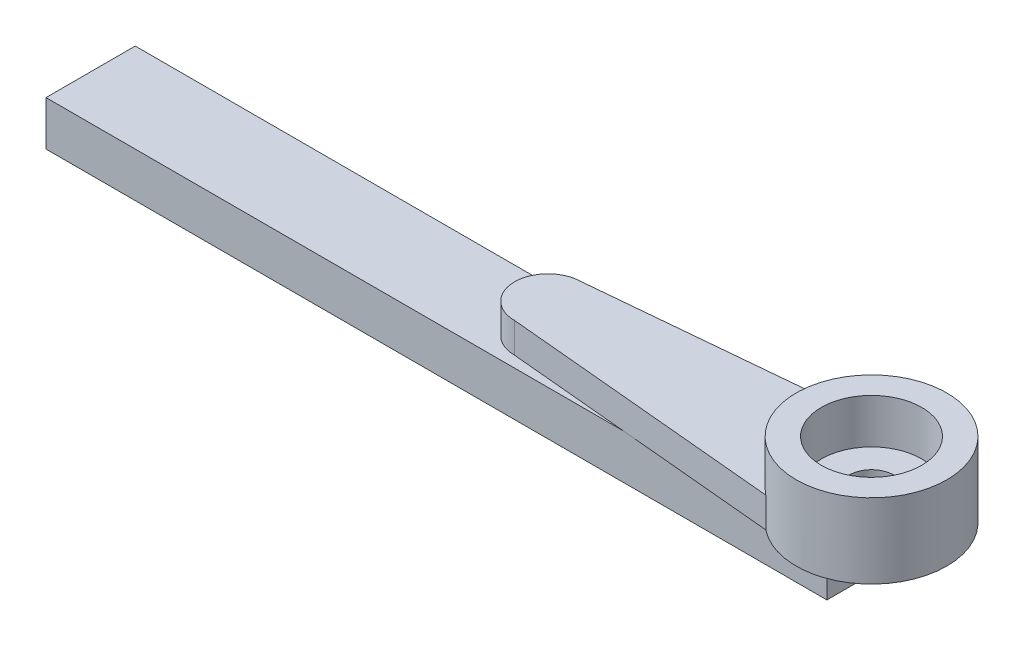
SolidWorks part; units mm, degrees
ref_plane "Piano frontale" through (0, 0, 0) normal (0, 0, 1) x (1, 0, 0)
ref_plane "Piano superiore" through (0, 0, 0) normal (0, 1, 0) x (1, 0, 0)
ref_plane "Piano destro" through (0, 0, 0) normal (1, 0, 0) x (0, 0, -1)
sketch "Schizzo1" plane through (0, 0, 0) normal (0, 1, 0) x (1, 0, 0)
  line L0 (-2.09, 2.65) -> (-14.5, 1.5)
  line L1 (-2.09, -2.65) -> (-14.5, -1.5)
  line L2 (-2.09, 2.65) -> (-2.09, -2.65)
  circle A0 centre (0, 0) radius 3.375
  arc A1 (-14.5, 1.5) -> (-14.5, -1.5) centre (-14.5, 0) ccw
  point P8 (-2.09, 0)
  point P13 (-16, 0)
  dimension "D1" = 6.75
  dimension "D3" = 1.5
  dimension "D2" = 5.3
  dimension "D4" = 3
  dimension "D5" = 16
extrude "Estrusione-Estrusione1" add sketch "Schizzo1" along normal blind 1.35 contours L0 A1 L1 A0 | L2 A0 | L2 A0
sketch "Schizzo2" plane through (0, 1.35, 0) normal (0, 1, 0) x (1, 0, 0)
  circle A0 centre (0, 0) radius 3.375
extrude "Estrusione-Estrusione2" add sketch "Schizzo2" along normal blind 2
sketch "Schizzo3" plane through (0, 3.35, 0) normal (0, 1, 0) x (1, 0, 0)
  circle A0 centre (0, 0) radius 2.25
  dimension "D1" = 4.5
extrude "Taglio-Estrusione1" cut sketch "Schizzo3" against normal blind 2
sketch "Schizzo4" plane through (0, 1.35, 0) normal (0, 1, 0) x (1, 0, 0)
  circle A0 centre (0, 0) radius 1
  dimension "D1" = 2
extrude "Taglio-Estrusione2" cut sketch "Schizzo4" against normal through all
sketch "Schizzo6" plane through (0, 0, 0) normal (0, -1, 0) x (1, 0, 0)
  line L1 (0, -2) -> (-35, -2)
  line L2 (0, -2) -> (0, 2)
  line L3 (0, 2) -> (-35, 2)
  line L4 (-35, -2) -> (-35, 2)
  dimension "D1" = 35
  dimension "D2" = 4
extrude "Estrusione-Estrusione3" add sketch "Schizzo6" along normal blind 2
